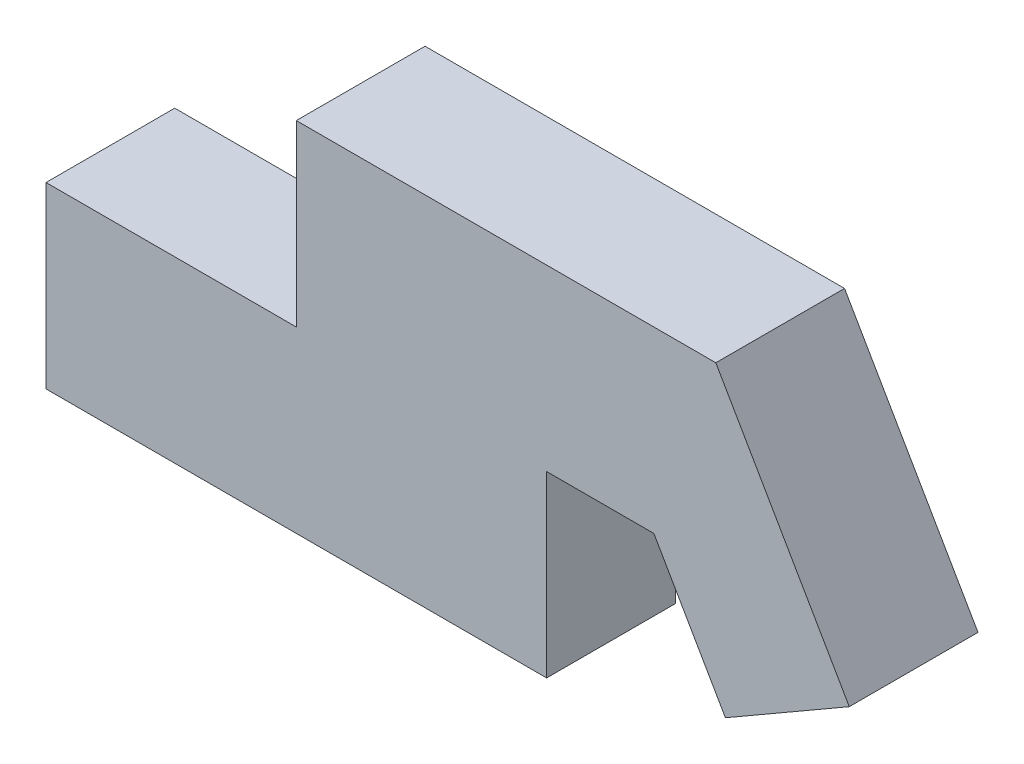
SolidWorks part; units mm, degrees
ref_plane "Plano frontal" through (0, 0, 0) normal (0, 0, 1) x (1, 0, 0)
ref_plane "Plano superior" through (0, 0, 0) normal (0, 1, 0) x (1, 0, 0)
ref_plane "Plano direito" through (0, 0, 0) normal (1, 0, 0) x (0, 0, -1)
sketch "Esboço1" plane through (0, 0, 0) normal (0, 0, 1) x (1, 0, 0)
  line L1 (70, 0) -> (70, 25)
  line L2 (70, 25) -> (85, 25)
  line L3 (85, 25) -> (95, 7.6795)
  line L4 (95, 7.6795) -> (112.3205, 17.6795)
  line L5 (112.3205, 17.6795) -> (93.6603, 50)
  line L6 (93.6603, 50) -> (35, 50)
  line L7 (35, 50) -> (35, 25)
  line L8 (35, 25) -> (0, 25)
  line L9 (0, 25) -> (0, 0)
  line L10 (0, 0) -> (70, 0)
  dimension "D1" = 70
  dimension "D2" = 35
  dimension "D3" = 25
  dimension "D4" = 15
  dimension "D5" = 120
  dimension "D6" = 20
  dimension "D7" = 20
extrude "Ressalto-extrusão1" add sketch "Esboço1" along normal blind 18 contours L10 L1 L2 L3 L4 L5 L6 L7 L8 L9
